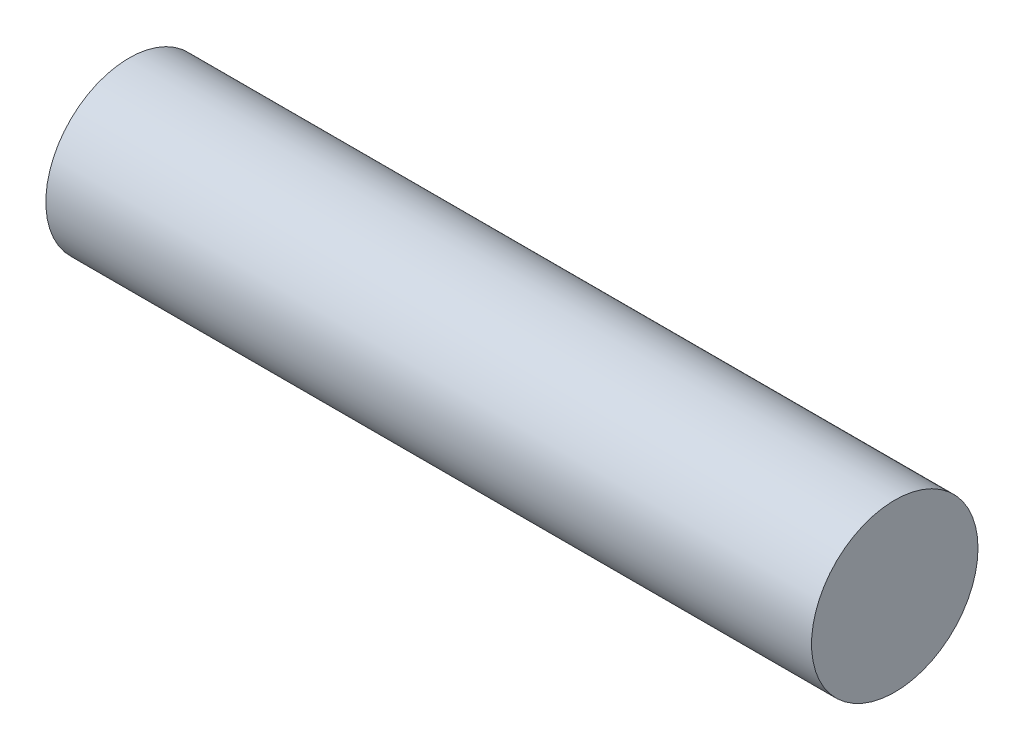
SolidWorks part; units mm, degrees
ref_plane "Front Plane" through (0, 0, 0) normal (0, 0, 1) x (1, 0, 0)
ref_plane "Top Plane" through (0, 0, 0) normal (0, 1, 0) x (1, 0, 0)
ref_plane "Right Plane" through (0, 0, 0) normal (1, 0, 0) x (0, 0, -1)
sketch "Profile Sketch" plane through (0, 0, 0) normal (1, 0, 0) x (0, 0, -1)
  circle A0 centre (0, 0) radius 5
  dimension "D1" = 10
extrude "Profile Extrude" add sketch "Profile Sketch" along normal blind 46
